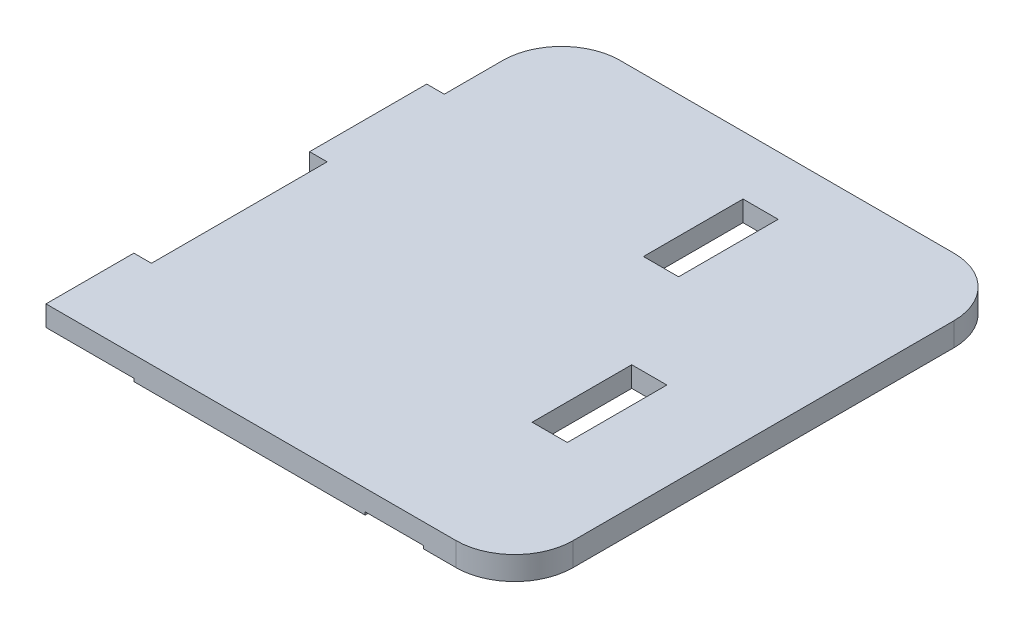
SolidWorks part; units mm, degrees
material "PBT General Purpose"
ref_plane "Front Plane" through (0, 0, 0) normal (0, 0, 1) x (1, 0, 0)
ref_plane "Top Plane" through (0, 0, 0) normal (0, 1, 0) x (1, 0, 0)
ref_plane "Right Plane" through (0, 0, 0) normal (1, 0, 0) x (0, 0, -1)
sketch "Sketch1" plane through (0, 0, 0) normal (0, 1, 0) x (1, 0, 0)
  line L0 (0, 0) -> (8, 0)
  line L5 (8, 0) -> (8, 8.5)
  line L6 (8, 8.5) -> (0.3, 8.5)
  line L7 (0.3, 8.5) -> (0.3, 6.5)
  line L8 (0.3, 6.5) -> (0, 6.5)
  line L9 (0, 6.5) -> (0, 4.5)
  line L10 (0, 4.5) -> (0.3, 4.5)
  line L11 (0.3, 4.5) -> (0.3, 1.5)
  line L12 (0.3, 1.5) -> (0, 1.5)
  line L13 (0, 1.5) -> (0, 0)
  line L15 (4.4, 7.5) -> (5, 7.5)
  line L16 (4.4, 7.5) -> (4.4, 5.8)
  line L17 (4.4, 5.8) -> (5, 5.8)
  line L18 (5, 7.5) -> (5, 5.8)
  line L19 (5.9, 2.4) -> (6.5, 2.4)
  line L20 (5.9, 2.4) -> (5.9, 4.1)
  line L21 (5.9, 4.1) -> (6.5, 4.1)
  line L22 (6.5, 2.4) -> (6.5, 4.1)
  dimension "D1" = 2
  dimension "D2" = 1.5
  dimension "D3" = 3
  dimension "D4" = 2
  dimension "D5" = 5.6
  dimension "D7" = 1.7
  dimension "D8" = 0.6
  dimension "D9" = 0.3
  dimension "D10" = 4.1
  dimension "D11" = 0.6
  dimension "D12" = 1.7
  dimension "D13" = 1
  dimension "D14" = 8
  dimension "D6" = 4.4
extrude "Boss-Extrude1" add sketch "Sketch1" along normal blind 0.4
fillet "Fillet2" radius 1 3 edges at (8, 0.2, 0) (8, 0.2, -8.5) (0.3, 0.2, -8.5)
sketch "Sketch2" plane through (0, 0, 0) normal (0, -1, 0) x (1, 0, 0)
  line L0 (5.9, -2.4) -> (5.9, -5.1) construction
  line L1 (6.4482, -2.4) -> (6.4482, -5.1)
  line L2 (5.4482, -2.4) -> (5.4482, -4.7094)
  line L3 (4.4, -5.8) -> (4.4, -8.5) construction
  line L4 (7, -8.5) -> (1.3, -8.5) construction
  line L5 (4.9, -5.8) -> (4.9, -8.5)
  line L6 (3.9, -5.8) -> (3.9, -8.5)
  line L7 (5.9792, -5.6424) -> (4.9, -5.8)
  line L8 (5.4482, -4.7094) -> (4.3278, -4.873)
  line L9 (6.4482, -2.4) -> (6.4482, 0)
  line L10 (0, 0) -> (7, 0) construction
  line L11 (6.4482, 0) -> (5.4482, 0)
  line L12 (5.4482, 0) -> (5.4482, -2.4)
  line L13 (3.9, -5.8) -> (3.9, -5.3677)
  line L14 (1.5, -8.5) -> (0, -8.5)
  line L15 (1.5, -8.5) -> (1.5, 0)
  line L16 (1.5, 0) -> (0, 0)
  line L17 (0, -8.5) -> (0, 0)
  arc A1 (5.9792, -5.6424) -> (6.4482, -5.1) centre (5.9, -5.1) ccw
  arc A3 (3.9, -8.5) -> (4.9, -8.5) centre (4.4, -8.5) ccw
  arc A4 (4.3278, -4.873) -> (3.9, -5.3677) centre (4.4, -5.3677) ccw
  point P3 (5.9, -3.75)
  point P8 (4.4, -7.15)
  dimension "D2" = 0.5482
  dimension "D3" = 1
  dimension "D6" = 0.5
  dimension "D1" = 2.7
  dimension "D4" = 1
  dimension "D5" = 1
  dimension "D7" = 1.5
extrude "Cut-Extrude1" cut sketch "Sketch2" against normal blind 0.05
equation "\"t\"= 0.3'thickness of the sheets"
equation "\"FlexJoint\"= 0.15'Width of flextures"
equation "\"FoldJoint\"= 0.4'Width of folding joints"
equation "\"AssembleAngle\"= 90'Angle of assembly parts"
equation "\"D9@Sketch1\"=\"t\""
